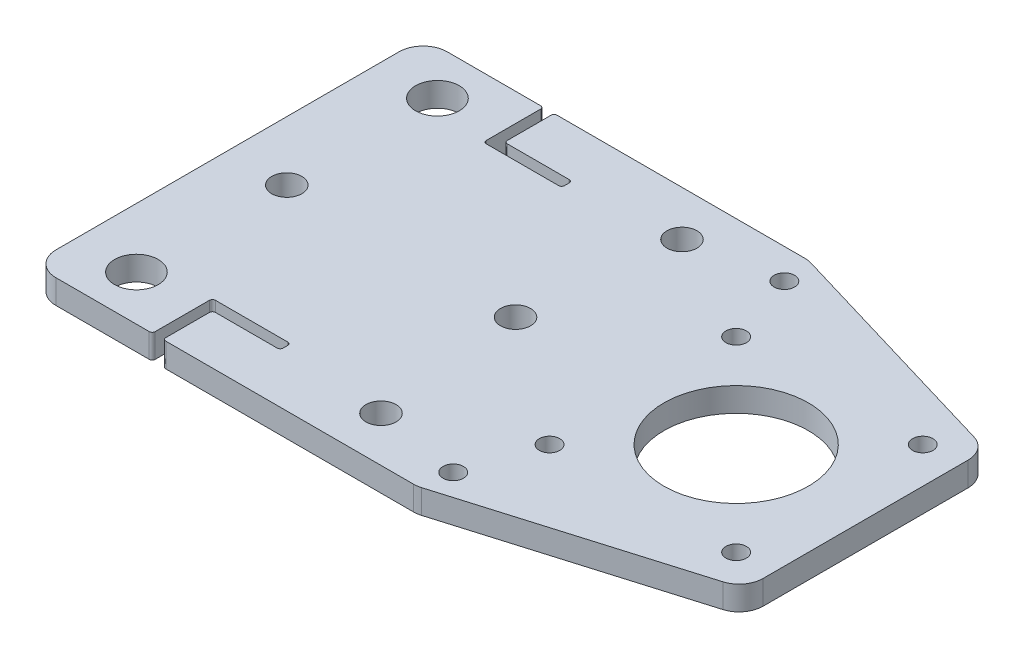
SolidWorks part; units mm, degrees
ref_plane "Front Plane" through (0, 0, 0) normal (0, 0, 1) x (1, 0, 0)
ref_plane "Top Plane" through (0, 0, 0) normal (0, 1, 0) x (1, 0, 0)
ref_plane "Right Plane" through (0, 0, 0) normal (1, 0, 0) x (0, 0, -1)
sketch "Sketch1" plane through (0, 0, 0) normal (0, 1, 0) x (1, 0, 0)
  line L0 (0, 0) -> (21.5, 0) construction
  line L5 (21.5, 20) -> (21.5, -20)
  line L6 (21.5, -20) -> (-20.5, -32.5)
  line L7 (-20.5, -32.5) -> (-84.5, -32.5)
  line L8 (-84.5, -32.5) -> (-84.5, 32.5)
  line L11 (-84.5, 32.5) -> (-20.5, 32.5)
  line L12 (-20.5, 32.5) -> (21.5, 20)
  circle A0 centre (0, 0) radius 12
  point P7 (21.5, 0)
  dimension "D4" = 24
  dimension "D6" = 9.5
  dimension "D1" = 40
  dimension "D2" = 106
  dimension "D3" = 65
  dimension "D5" = 64
extrude "Boss-Extrude1" add sketch "Sketch1" along normal mid plane 4
sketch "Sketch2" plane through (0, 2, 0) normal (0, 1, 0) x (1, 0, 0)
  line L0 (0, 0) -> (-19.5, 0) construction
  line L1 (-15.5, -15.5) -> (15.5, -15.5) construction
  line L2 (-15.5, -15.5) -> (-15.5, 15.5) construction
  line L3 (-15.5, 15.5) -> (15.5, 15.5) construction
  line L4 (15.5, -15.5) -> (15.5, 15.5) construction
  line L5 (-15.5, -15.5) -> (15.5, 15.5) construction
  line L6 (-15.5, 15.5) -> (15.5, -15.5) construction
  line L7 (-19.5, 27.5) -> (-19.5, -27.5) construction
  line L9 (-84.5, 32.5) -> (-84.5, -32.5) construction
  circle A0 centre (15.5, 15.5) radius 1.7
  circle A1 centre (-15.5, 15.5) radius 1.7
  circle A2 centre (-15.5, -15.5) radius 1.7
  circle A3 centre (15.5, -15.5) radius 1.7
  circle A4 centre (-19.5, 27.5) radius 1.7
  circle A5 centre (-19.5, -27.5) radius 1.7
  point P0 (0, 0)
  dimension "D2" = 3.4
  dimension "D1" = 31
  dimension "D3" = 55
  dimension "D4" = 65
extrude "Cut-Extrude1" cut sketch "Sketch2" against normal through all
sketch "Sketch3" plane through (0, 2, 0) normal (0, 1, 0) x (1, 0, 0)
  line L0 (0, 0) -> (-84.5, 0) construction
  line L1 (-84.5, 32.5) -> (-84.5, -32.5) construction
  line L2 (-34, 25) -> (-34, -25) construction
  line L3 (-34, 25) -> (-74.625, 25) construction
  line L4 (-34, -25) -> (-74.625, -25) construction
  circle A0 centre (-74.65, 0) radius 2.5
  circle A1 centre (-36.65, 0) radius 2.5
  circle A2 centre (-34, 25) radius 2.5
  circle A3 centre (-34, -25) radius 2.5
  circle A4 centre (-74.625, 25) radius 3.625
  circle A5 centre (-74.625, -25) radius 3.625
  point P7 (-34, 0)
  dimension "D1" = 5
  dimension "D4" = 7.35
  dimension "D6" = 7.25
  dimension "D7" = 34.5
  dimension "D2" = 50
  dimension "D3" = 38
  dimension "D5" = 48
extrude "Cut-Extrude2" cut sketch "Sketch3" against normal through all
sketch "Sketch4" plane through (0, 2, 0) normal (0, 1, 0) x (1, 0, 0)
  line L0 (-64.5, 32.5) -> (-64.5, 22.5)
  line L1 (-20.5, 32.5) -> (-84.5, 32.5) construction
  line L2 (-64.5, 22.5) -> (-51.5, 22.5)
  line L3 (-51.5, 22.5) -> (-51.5, 24.25)
  line L4 (-51.5, 24.25) -> (-62.75, 24.25)
  line L5 (-62.75, 24.25) -> (-62.75, 32.5)
  line L6 (-62.75, 32.5) -> (-64.5, 32.5)
  line L7 (-84.5, 32.5) -> (-84.5, -32.5) construction
  line L8 (0, 0) -> (-84.5, 0) construction
  line L9 (-62.75, -24.25) -> (-62.75, -32.5)
  line L10 (-51.5, -24.25) -> (-62.75, -24.25)
  line L11 (-51.5, -22.5) -> (-51.5, -24.25)
  line L12 (-64.5, -22.5) -> (-51.5, -22.5)
  line L13 (-64.5, -32.5) -> (-64.5, -22.5)
  line L14 (-62.75, -32.5) -> (-64.5, -32.5)
  dimension "D1" = 1.75
  dimension "D2" = 10
  dimension "D3" = 13
  dimension "D4" = 20
extrude "Cut-Extrude3" cut sketch "Sketch4" against normal through all
fillet "Fillet1" radius 4 6 edges at (-84.5, 0, -32.5) (-84.5, 0, 32.5) (-20.5, 0, 32.5) (21.5, 0, 20) (-20.5, 0, -32.5) (21.5, 0, -20)
fillet "Fillet2" radius 0.5 12 edges at (-64.5, 0, 32.5) (-64.5, 0, 22.5) (-51.5, 0, 22.5) (-51.5, 0, 24.25) (-62.75, 0, 24.25) (-62.75, 0, 32.5) (-62.75, 0, -32.5) (-62.75, 0, -24.25) (-51.5, 0, -24.25) (-51.5, 0, -22.5) (-64.5, 0, -22.5) (-64.5, 0, -32.5)
sketch "Sketch5" [suppressed] plane through (0, 2, 0) normal (0, 1, 0) x (1, 0, 0)
  line L0 (-24.5, 32.5) -> (-24.5, 10)
  line L1 (-21.0826, 32.5) -> (-62.25, 32.5) construction
  line L2 (-62.25, -32.5) -> (-21.0826, -32.5) construction
  line L3 (-84.5, 28.5) -> (-84.5, -28.5) construction
  line L4 (-24.5, 32.5) -> (26.912, 32.5)
  line L5 (-24.5, -10) -> (-29.5, -10)
  line L6 (-24.5, -10) -> (-24.5, 10) construction
  line L7 (-24.5, 10) -> (-29.5, 10)
  line L8 (-29.5, -10) -> (-29.5, 10)
  line L9 (26.912, 32.5) -> (26.912, -32.5)
  line L11 (-24.5, -32.5) -> (26.912, -32.5)
  line L12 (-24.5, 10) -> (-24.5, -10) construction
  line L13 (-24.5, -10) -> (-24.5, -32.5)
  line L14 (-29.5, 0) -> (0, 0) construction
  dimension "D1" = 60
  dimension "D2" = 20
  dimension "D3" = 5
extrude "Cut-Extrude4" [suppressed] cut sketch "Sketch5" against normal through all contours L8 L5 L0 L7
fillet "Fillet3" [suppressed] radius 4
fillet "Fillet4" [suppressed] radius 2
